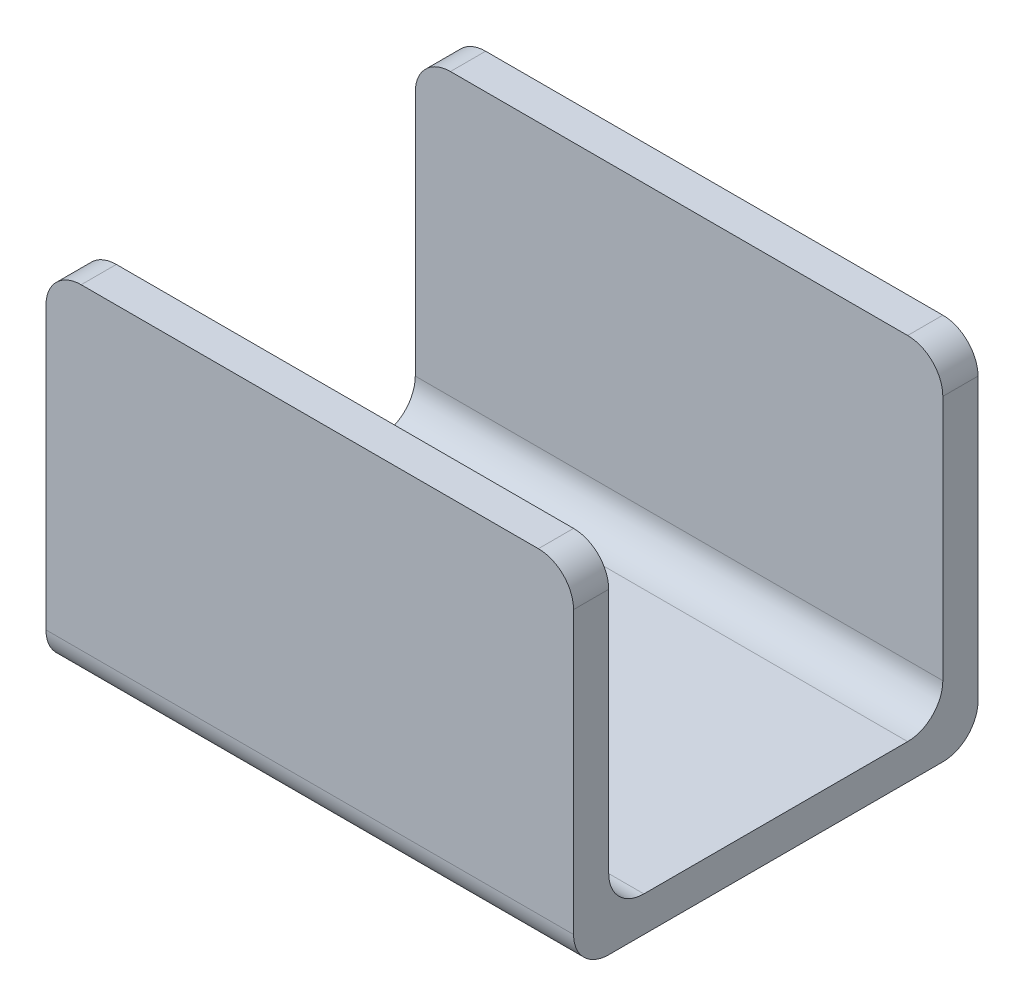
SolidWorks part; units mm, degrees
ref_plane "Vorderansicht" through (0, 0, 0) normal (0, 0, 1) x (1, 0, 0)
ref_plane "Draufsicht" through (0, 0, 0) normal (0, 1, 0) x (1, 0, 0)
ref_plane "Seitenansicht" through (0, 0, 0) normal (1, 0, 0) x (0, 0, -1)
sketch "Skizze1" plane through (0, 0, 0) normal (1, 0, 0) x (0, 0, -1)
  line L0 (-23, 40) -> (-19, 40)
  line L1 (-19, 40) -> (-19, 4)
  line L2 (-19, 4) -> (19, 4)
  line L3 (19, 4) -> (19, 40)
  line L4 (19, 40) -> (23, 40)
  line L5 (23, 40) -> (23, 0)
  line L6 (23, 0) -> (-23, 0)
  line L7 (-23, 0) -> (-23, 40)
  point P2 (0, 0)
  point P10 (-32.3077, 2.3654)
  point P11 (21, 40)
  dimension "D1" = 4
  dimension "D2" = 4
  dimension "D3" = 4
  dimension "D4" = 40
  dimension "D5" = 38
  dimension "D6" = 40
extrude "Aufsatz-Linear austragen1" add sketch "Skizze1" against normal mid plane 60
fillet "Verrundung1" radius 4 1 edges at (0, 0, -23)
fillet "Verrundung2" radius 4 1 edges at (0, 0, 23)
fillet "Verrundung3" radius 4 1 edges at (-30, 40, -21)
fillet "Verrundung4" radius 4 1 edges at (30, 40, -21)
fillet "Verrundung5" radius 4 2 edges at (30, 40, 21) (-30, 40, 21)
fillet "Verrundung6" radius 4 1 edges at (0, 4, 19)
fillet "Verrundung7" radius 4 1 edges at (0, 4, -19)
